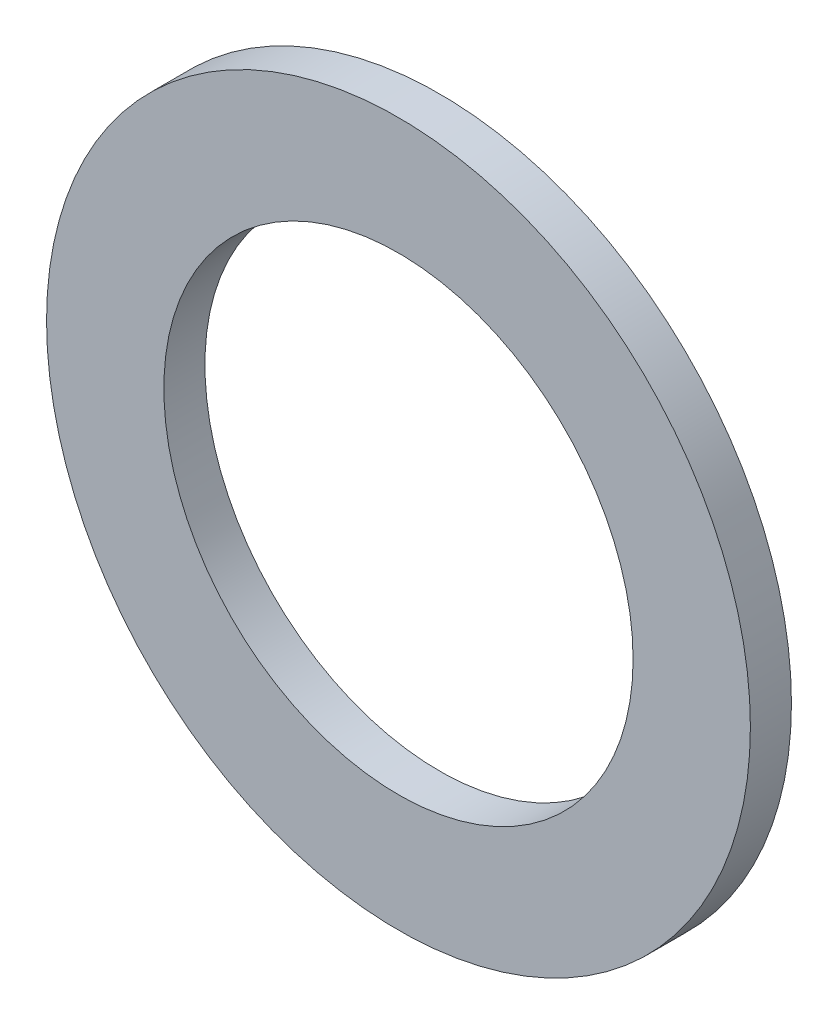
SolidWorks part; units mm, degrees
material "PTFE (general)"
ref_plane "Front Plane" through (0, 0, 0) normal (0, 0, 1) x (1, 0, 0)
ref_plane "Top Plane" through (0, 0, 0) normal (0, 1, 0) x (1, 0, 0)
ref_plane "Right Plane" through (0, 0, 0) normal (1, 0, 0) x (0, 0, -1)
sketch "Sketch1" plane through (0, 0, 0) normal (0, 0, 1) x (1, 0, 0)
  circle A0 centre (0, 0) radius 20
  circle A1 centre (0, 0) radius 30
  dimension "D1" = 40
  dimension "D2" = 60
extrude "Boss-Extrude1" add sketch "Sketch1" along normal blind 3.5
